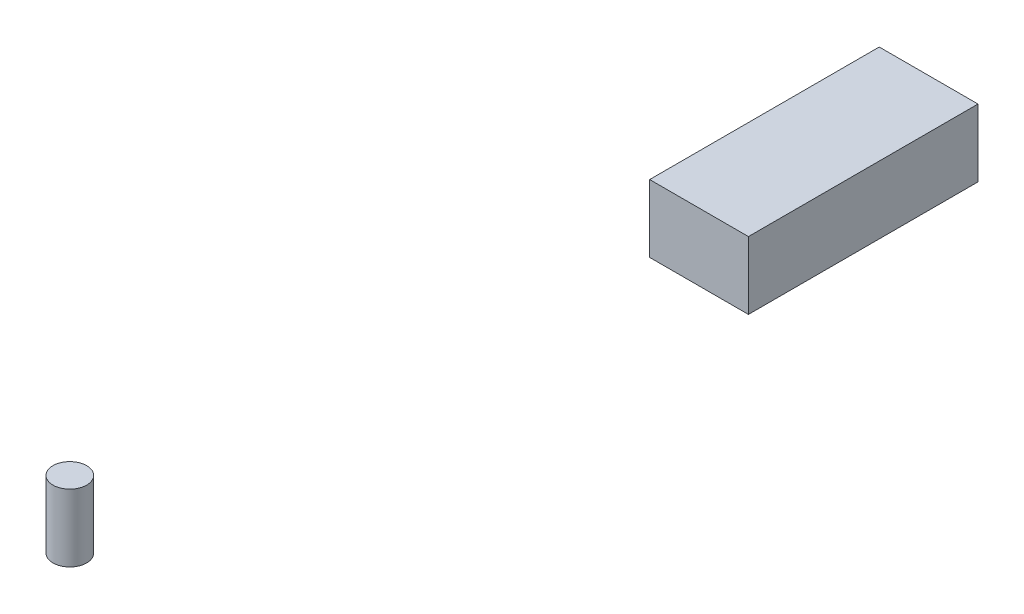
SolidWorks part; units mm, degrees
material "Aleación 1060"
ref_plane "Alzado" through (0, 0, 0) normal (0, 0, 1) x (1, 0, 0)
ref_plane "Planta" through (0, 0, 0) normal (0, 1, 0) x (1, 0, 0)
ref_plane "Vista lateral" through (0, 0, 0) normal (1, 0, 0) x (0, 0, -1)
sketch "Croquis1" plane through (0, 0, 0) normal (0, 1, 0) x (1, 0, 0)
  circle A0 centre (0, 0) radius 2.5
  dimension "D1" = 5
extrude "Saliente-Extruir1" add sketch "Croquis1" along normal blind 10 contours A0
sketch "Croquis2" plane through (0, 0, 0) normal (0, 1, 0) x (1, 0, 0)
  line L0 (0, 0) -> (5, 0) construction
  line L1 (5, 0) -> (5, 114.995) construction
  line L3 (5, 114.995) -> (19.6415, 114.995)
  line L4 (5, 114.995) -> (5, 80.9607)
  line L5 (5, 80.9607) -> (19.6415, 80.9607)
  line L6 (19.6415, 114.995) -> (19.6415, 80.9607)
  dimension "D1" = 5
extrude "Saliente-Extruir2" add sketch "Croquis2" along normal blind 10 separate body
